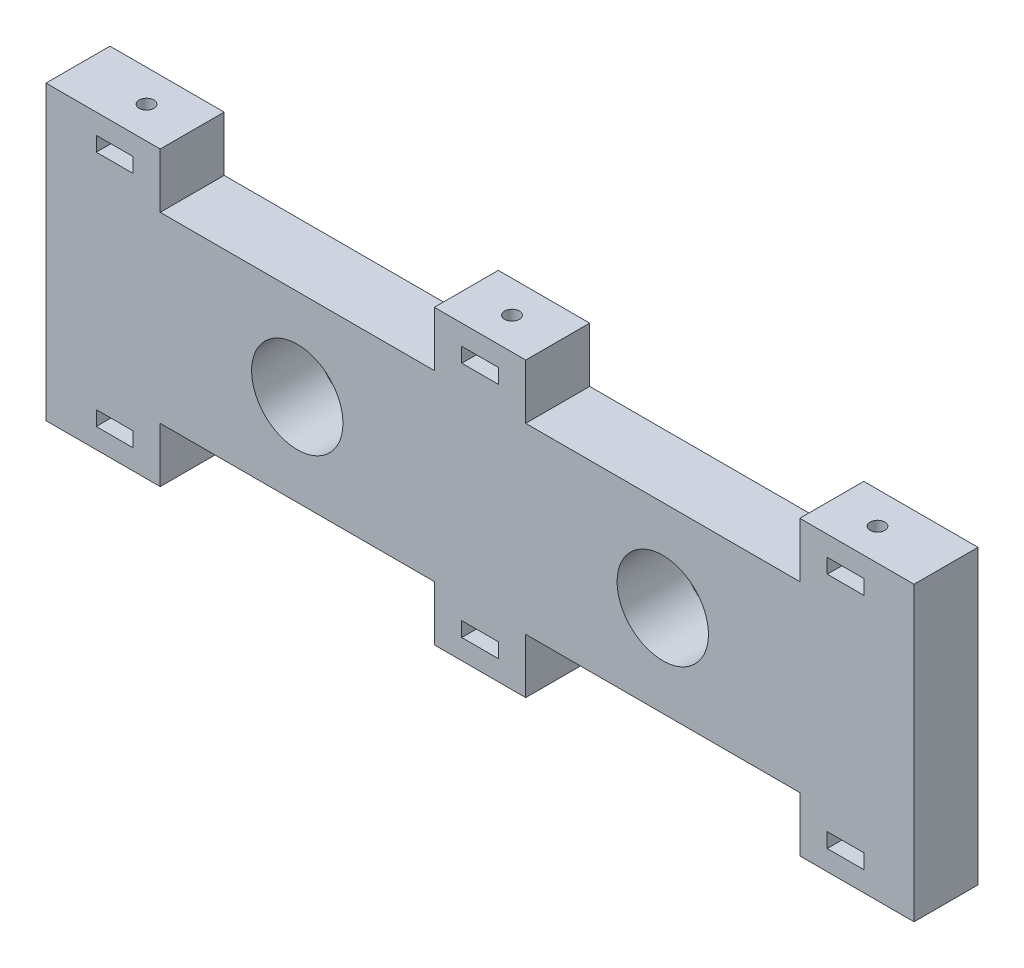
SolidWorks part; units mm, degrees
ref_plane "Front" through (0, 0, 0) normal (0, 0, 1) x (1, 0, 0)
ref_plane "Top" through (0, 0, 0) normal (0, 1, 0) x (1, 0, 0)
ref_plane "Right" through (0, 0, 0) normal (1, 0, 0) x (0, 0, -1)
sketch "草图1" plane through (0, 0, 0) normal (0, 0, 1) x (1, 0, 0)
  line L0 (-15, 10) -> (-15, 16)
  line L1 (25, -16) -> (15, -16)
  line L2 (40, 16) -> (40, -16) construction
  line L3 (25, 16) -> (15, 16)
  line L4 (-27.5, -16) -> (-27.5, 16)
  line L5 (0, 16) -> (0, -16) construction
  line L6 (15, 10) -> (15, 16)
  line L7 (-15, -10) -> (15, -10)
  line L8 (-15, 16) -> (-27.5, 16)
  line L9 (-15, 10) -> (15, 10)
  line L10 (20, 16) -> (20, -16) construction
  line L11 (-15, -10) -> (-15, -16)
  line L12 (15, -10) -> (15, -16)
  line L13 (-15, -16) -> (-27.5, -16)
  line L14 (40, 16) -> (40, -16) construction
  line L15 (60, 16) -> (60, -16) construction
  line L16 (55, -16) -> (67.5, -16)
  line L17 (25, -10) -> (25, -16)
  line L18 (55, -10) -> (55, -16)
  line L19 (55, 10) -> (25, 10)
  line L20 (55, 16) -> (67.5, 16)
  line L21 (55, -10) -> (25, -10)
  line L22 (25, 10) -> (25, 16)
  line L23 (67.5, -16) -> (67.5, 16)
  line L24 (55, 10) -> (55, 16)
  circle A0 centre (0, 0) radius 5
  circle A1 centre (40, 0) radius 5
  point P0 (0, 0)
  point P6 (0, 0)
  dimension "D1" = 4
extrude "凸台-拉伸1" add sketch "草图1" along normal blind 7
sketch "草图2" plane through (0, 16, 0) normal (0, 1, 0) x (1, 0, 0)
  line L0 (-27.5, -3.5) -> (67.5, -3.5) construction
  line L3 (0, 0) -> (0, -7) construction
  line L4 (15, -7) -> (-15, -7) construction
  line L5 (-27.5, -7) -> (-27.5, 0) construction
  line L6 (67.5, -7) -> (67.5, 0) construction
  line L7 (-20, 0) -> (-20, -7) construction
  line L8 (20, 0) -> (20, -7) construction
  line L9 (40, 0) -> (40, -7) construction
  line L10 (60, 0) -> (60, -7) construction
  point P16 (-20, -3.5)
  point P22 (20, -3.5)
  point P23 (60, -3.5)
  dimension "D1" = 2
  dimension "D2" = 4
ref_plane "基准面1" through (0, 13, 0) normal (0, 1, 0) x (1, 0, 0)
ref_plane "基准面2" through (0, -13, 0) normal (0, -1, 0) x (-1, 0, 0)
hole_wizard "M2x0.4 螺纹孔1" positions "3D草图2" profile "草图3" tap size "M2x0.4" standard "ANSI Metric" end condition through all
sketch3d "3D草图2"
  point P0 (-20, 16, 3.5)
  point P3 (20, 16, 3.5)
  point P6 (60, 16, 3.5)
sketch "草图3" plane through (-20, 16, 3.5) normal (1, 0, 0) x (0, 0, 1)
  line L0 (0, 0) -> (0, 32)
  line L1 (0, 32) -> (0.8, 32)
  line L2 (0.8, 32) -> (0.8, 0)
  line L5 (0.8, 0) -> (0, 0)
  line L11 (0, -6.35) -> (0, 107.95) construction
  dimension "通孔螺纹孔钻头直径" = 1.6
  dimension "通孔螺纹孔钻头深度" = 32
cosmetic thread "孔螺蚊线1" parameters "D2"=2
cosmetic thread "孔螺蚊线2" parameters "D2"=2
cosmetic thread "孔螺蚊线3" parameters "D2"=2
sketch "草图4" plane through (0, 13, 0) normal (0, 1, 0) x (1, 0, 0)
  line L0 (-22, -4.6547) -> (-22, -7)
  line L1 (-20, -1.1906) -> (-22, -2.3453)
  line L2 (-22, -2.3453) -> (-22, -4.6547)
  line L3 (-22, -7) -> (-18, -7)
  line L4 (18, -4.6547) -> (18, -7)
  line L5 (-18, -4.6547) -> (-18, -2.3453)
  line L6 (-18, -2.3453) -> (-20, -1.1906)
  line L7 (-15, -7) -> (-27.5, -7) construction
  line L8 (-18, -7) -> (-18, -4.6547)
  line L9 (20, -1.1906) -> (18, -2.3453)
  line L10 (-20, -5.8094) -> (-18, -4.6547) [skipped]
  line L11 (-22, -4.6547) -> (-20, -5.8094) [skipped]
  line L12 (18, -2.3453) -> (18, -4.6547)
  line L13 (18, -7) -> (22, -7)
  line L14 (22, -4.6547) -> (22, -2.3453)
  line L15 (22, -2.3453) -> (20, -1.1906)
  line L16 (22, -7) -> (22, -4.6547)
  line L17 (58, -4.6547) -> (58, -7)
  line L18 (60, -1.1906) -> (58, -2.3453)
  line L19 (58, -2.3453) -> (58, -4.6547)
  line L20 (58, -7) -> (62, -7)
  line L21 (62, -4.6547) -> (62, -2.3453)
  line L22 (62, -2.3453) -> (60, -1.1906)
  line L23 (62, -7) -> (62, -4.6547)
  circle A0 centre (-20, -3.5) radius 2 construction
  circle A1 centre (20, -3.5) radius 2 construction
  circle A2 centre (60, -3.5) radius 2 construction
  dimension "D1" = 3
extrude "切除-拉伸1" cut sketch "草图4" against normal mid plane 1.6
sketch "草图5" plane through (0, -13, 0) normal (0, -1, 0) x (-1, 0, 0)
  line L0 (-20, -1.1906) -> (-22, -2.3453)
  line L1 (-60, -1.1906) -> (-62, -2.3453)
  line L2 (-62, -2.3453) -> (-62, -4.6547)
  line L3 (-22, -2.3453) -> (-22, -4.6547)
  line L4 (-18, -4.6547) -> (-18, -2.3453)
  line L5 (-58, -4.6547) -> (-58, -2.3453)
  line L6 (-58, -2.3453) -> (-60, -1.1906)
  line L7 (-18, -2.3453) -> (-20, -1.1906)
  line L8 (-62, -4.6547) -> (-62, -7)
  line L9 (-62, -7) -> (-58, -7)
  line L10 (-58, -4.6547) -> (-58, -7)
  line L11 (-60, -5.8094) -> (-58, -4.6547) [skipped]
  line L12 (-62, -4.6547) -> (-60, -5.8094) [skipped]
  line L13 (-22, -4.6547) -> (-22, -7)
  line L14 (-22, -7) -> (-18, -7)
  line L15 (-18, -4.6547) -> (-18, -7)
  line L16 (20, -1.1906) -> (18, -2.3453)
  line L17 (18, -2.3453) -> (18, -4.6547)
  line L18 (22, -4.6547) -> (22, -2.3453)
  line L19 (22, -2.3453) -> (20, -1.1906)
  line L20 (18, -4.6547) -> (18, -7)
  line L21 (18, -7) -> (22, -7)
  line L22 (22, -4.6547) -> (22, -7)
  circle A0 centre (-60, -3.5) radius 2 construction
  circle A1 centre (-20, -3.5) radius 2 construction
  circle A2 centre (20, -3.5) radius 2 construction
  dimension "D1" = 3
extrude "切除-拉伸2" cut sketch "草图5" against normal mid plane 1.6
